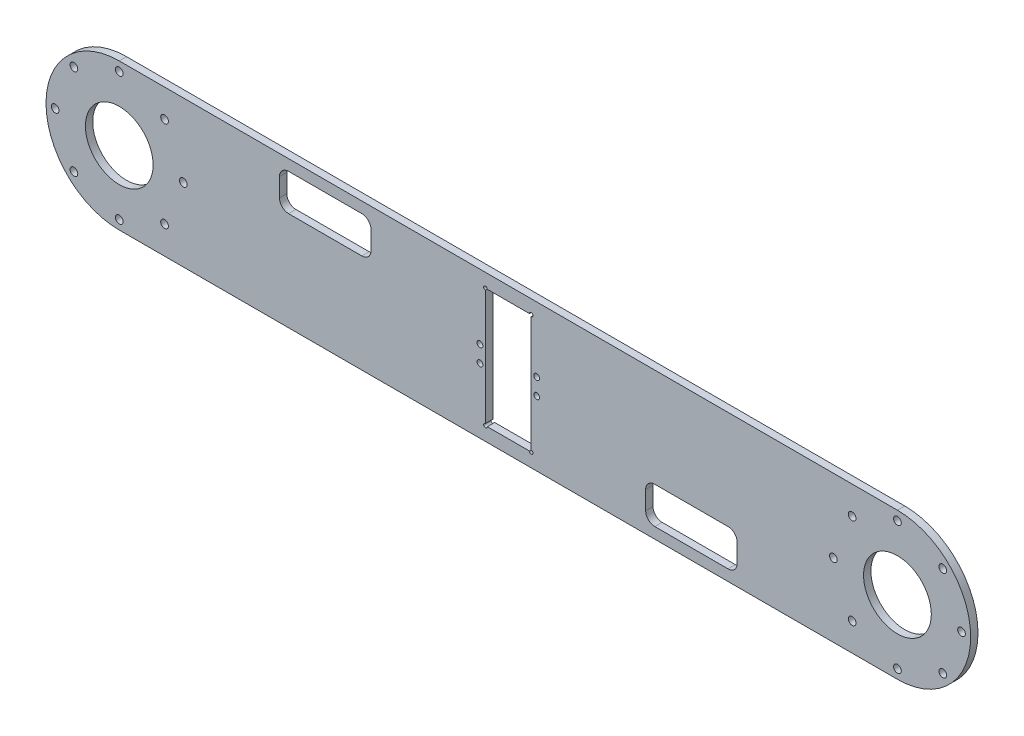
SolidWorks part; units mm, degrees
material "Thornel Mat VMA"
ref_plane "前视基准面" through (0, 0, 0) normal (0, 0, 1) x (1, 0, 0)
ref_plane "上视基准面" through (0, 0, 0) normal (0, 1, 0) x (1, 0, 0)
ref_plane "右视基准面" through (0, 0, 0) normal (1, 0, 0) x (0, 0, -1)
other "Configuration Table"
sketch "草图1" plane through (0, 0, 0) normal (0, 0, 1) x (1, 0, 0)
  line L0 (-212.5, 40) -> (212.5, 40)
  line L1 (-212.5, -40) -> (212.5, -40) construction
  line L2 (-212.5, -40) -> (-212.5, 40) construction
  line L3 (-212.5, 40) -> (212.5, 40) construction
  line L4 (212.5, -40) -> (212.5, 40) construction
  line L5 (0, 40) -> (0, -40) construction
  line L6 (-212.5, 0) -> (212.5, 0) construction
  line L7 (-212.5, -40) -> (212.5, -40)
  arc A0 (-212.5, 40) -> (-212.5, -40) centre (-212.5, 0) ccw
  arc A1 (212.5, -40) -> (212.5, 40) centre (212.5, 0) ccw
  point P0 (0, 0)
  dimension "D1" = 425
  dimension "D2" = 80
extrude "凸台-拉伸1" add sketch "草图1" along normal blind 4
sketch "草图3" plane through (0, 0, 4) normal (0, 0, 1) x (1, 0, 0)
  circle A0 centre (-212.5, 0) radius 18.5
  circle A1 centre (212.5, 0) radius 18.5
  dimension "D1" = 37
  dimension "D2" = 37
extrude "切除-拉伸2" cut sketch "草图3" against normal through all
sketch "草图6" plane through (0, 0, 0) normal (0, 0, -1) x (-1, 0, 0)
  circle A0 centre (-212.5, 0) radius 35 construction
  circle A1 centre (-247.5, 0) radius 2.1
  circle A2 centre (-237.2487, 24.7487) radius 2.1
  circle A3 centre (-212.5, 35) radius 2.1
  circle A4 centre (-187.7513, 24.7487) radius 2.1
  circle A5 centre (-177.5, 0) radius 2.1
  circle A6 centre (-187.7513, -24.7487) radius 2.1
  circle A7 centre (-212.5, -35) radius 2.1
  circle A8 centre (-237.2487, -24.7487) radius 2.1
  point P21 (-212.5, 0)
  dimension "D1" = 70
  dimension "D2" = 4.2
  dimension "D3" = 8
extrude "切除-拉伸5" cut sketch "草图6" against normal through all
mirror "镜向1" about plane through (0, 0, 0) normal (1, 0, 0) of "切除-拉伸5"
sketch "草图7" plane through (0, 0, 0) normal (0, 0, -1) x (-1, 0, 0)
  line L1 (-12.5, 32.5) -> (12.5, 32.5)
  line L2 (-12.5, 32.5) -> (-12.5, -32.5)
  line L3 (-12.5, -32.5) -> (12.5, -32.5)
  line L4 (12.5, 32.5) -> (12.5, -32.5)
  line L5 (0, -32.5) -> (0, 32.5) construction
  line L6 (-12.5, 0) -> (12.5, 0) construction
  point P0 (0, 0)
  dimension "D1" = 65
  dimension "D2" = 25
extrude "切除-拉伸6" cut sketch "草图7" against normal through all
sketch "草图8" plane through (0, 0, 0) normal (0, 0, -1) x (-1, 0, 0)
  circle A0 centre (-12.5, 32.5) radius 1
  circle A1 centre (12.5, 32.5) radius 1
  circle A2 centre (-12.5, -32.5) radius 1
  circle A3 centre (12.5, -32.5) radius 1
  dimension "D1" = 2
extrude "切除-拉伸7" cut sketch "草图8" against normal through all
sketch "草图9" plane through (0, 0, 0) normal (0, 0, -1) x (-1, 0, 0)
  line L0 (0, 0) -> (0, 32.5) construction
  line L1 (11.5, 32.5) -> (-11.5, 32.5) construction
  line L2 (0, 0) -> (-12.5, 0) construction
  line L3 (-12.5, 31.5) -> (-12.5, -31.5) construction
  circle A0 centre (-15.5, -4.5) radius 1.6
  circle A1 centre (-15.5, 4.5) radius 1.6
  circle A2 centre (15.5, -4.5) radius 1.6
  circle A3 centre (15.5, 4.5) radius 1.6
  point P12 (-9.8152, 0)
  dimension "D1" = 3.2
  dimension "D2" = 3
  dimension "D3" = 9
extrude "切除-拉伸8" cut sketch "草图9" against normal through all
sketch "草图10" plane through (0, 0, 4) normal (0, 0, 1) x (1, 0, 0)
  line L0 (-212.5, -40) -> (212.5, -40) construction
  line L1 (75, -34) -> (125, -34)
  line L2 (75, -34) -> (75, -14)
  line L3 (75, -14) -> (125, -14)
  line L4 (125, -34) -> (125, -14)
  line L5 (0, 40) -> (0, -40) construction
  line L6 (212.5, 40) -> (-212.5, 40) construction
  line L7 (-252.5, 0) -> (0, 0) construction
  line L8 (-75, -14) -> (-125, -14) construction
  line L9 (-125, -34) -> (-125, -14) construction
  line L10 (-75, -34) -> (-125, -34) construction
  line L11 (-75, -34) -> (-75, -14) construction
  line L12 (-75, 34) -> (-75, 14)
  line L13 (-75, 34) -> (-125, 34)
  line L14 (-125, 34) -> (-125, 14)
  line L15 (-75, 14) -> (-125, 14)
  arc A0 (-212.5, 40) -> (-212.5, -40) centre (-212.5, 0) ccw construction
  dimension "D1" = 26
  dimension "D2" = 20
  dimension "D3" = 50
  dimension "D4" = 75
extrude "切除-拉伸9" cut sketch "草图10" against normal through all
fillet "圆角2" radius 5 8 edges at (125, -14, 2) (75, -14, 2) (125, -34, 2) (75, -34, 2) (-125, 14, 2) (-125, 34, 2) (-75, 34, 2) (-75, 14, 2)
